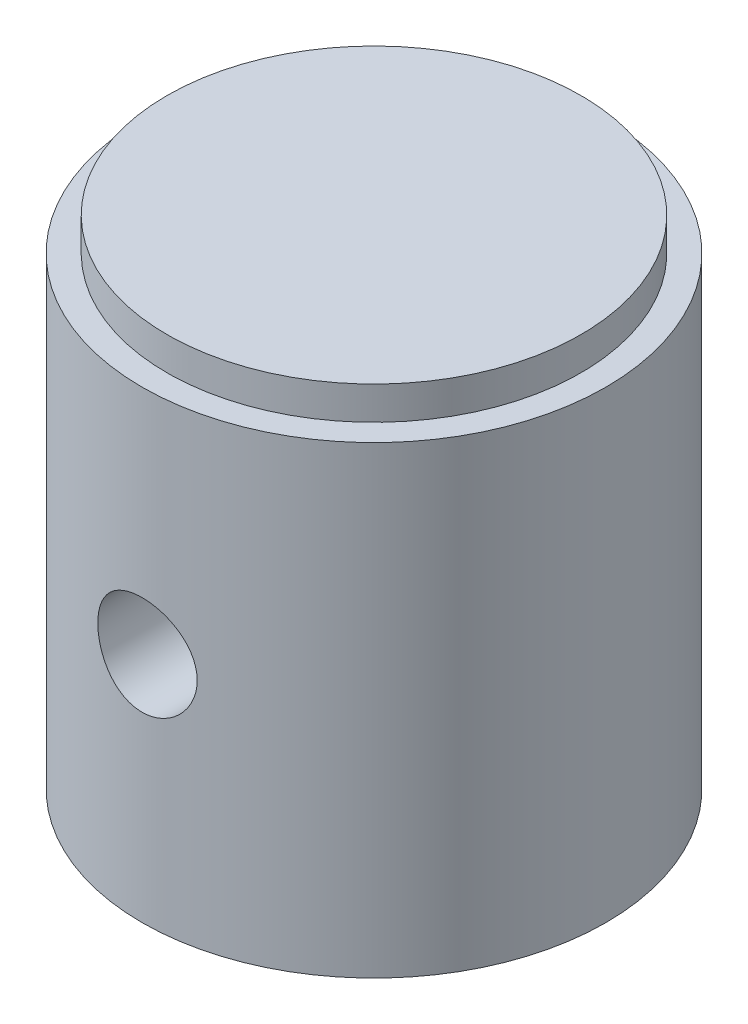
SolidWorks part; units mm, degrees
ref_plane "Front Plane" through (0, 0, 0) normal (0, 0, 1) x (1, 0, 0)
ref_plane "Top Plane" through (0, 0, 0) normal (0, 1, 0) x (1, 0, 0)
ref_plane "Right Plane" through (0, 0, 0) normal (1, 0, 0) x (0, 0, -1)
sketch "Sketch1" plane through (0, 0, 0) normal (0, 0, 1) x (1, 0, 0)
  line L0 (0, 1.1459) -> (0, -10.1408) construction
  line L1 (0, 1.1459) -> (-6.25, 1.1459)
  line L2 (-6.25, 1.1459) -> (-6.25, 0.1459)
  line L3 (-6.25, 0.1459) -> (-7, 0.1459)
  line L4 (-7, 0.1459) -> (-7, -13.8541)
  line L5 (-6.25, -13.8541) -> (-4.75, -9.7329)
  line L6 (-4.75, -9.7329) -> (-4.75, -2.8541)
  line L7 (-4.75, -2.8541) -> (0, 0)
  line L8 (0, 0) -> (0, 1.1459)
  line L9 (-7, -13.8541) -> (-6.25, -13.8541)
  point P3 (0, 0)
  point P12 (0, 0)
  point P13 (-5.2154, -4.4848)
  dimension "D1" = 7
  dimension "D2" = 6.25
  dimension "D3" = 15
  dimension "D4" = 1
  dimension "D5" = 6.25
  dimension "D6" = 4.75
  dimension "D7" = 20
  dimension "D8" = 59
  dimension "D9" = 11
revolve "Revolve1" add sketch "Sketch1" angle 360 about L0
sketch "Sketch2" plane through (0, 0, 0) normal (0, 0, 1) x (1, 0, 0)
  line L0 (-7, -13.8541) -> (7, -13.8541) construction
  circle A0 centre (0, -6.8541) radius 1.5
  point P5 (0, 0)
  dimension "D1" = 3
  dimension "D2" = 7
extrude "Cut-Extrude1" cut sketch "Sketch2" against normal through all both and the other way through all
